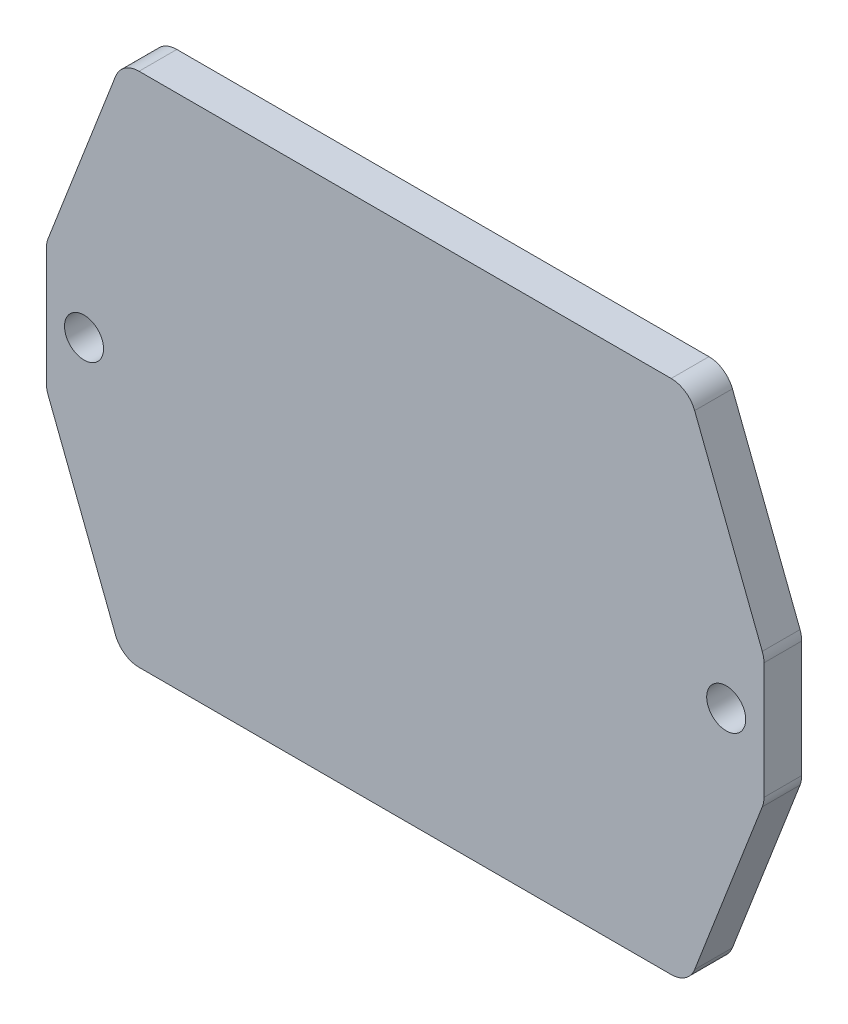
SolidWorks part; units mm, degrees
ref_plane "前视基准面" through (0, 0, 0) normal (0, 0, 1) x (1, 0, 0)
ref_plane "上视基准面" through (0, 0, 0) normal (0, 1, 0) x (1, 0, 0)
ref_plane "右视基准面" through (0, 0, 0) normal (1, 0, 0) x (0, 0, -1)
sketch "草图1" plane through (0, 0, 0) normal (0, 0, 1) x (1, 0, 0)
  line L1 (-22.5, -20.5) -> (22.5, -20.5)
  line L2 (-22.5, -20.5) -> (-22.5, 20.5)
  line L3 (-22.5, 20.5) -> (22.5, 20.5)
  line L4 (22.5, -20.5) -> (22.5, 20.5)
  line L5 (0, 20.5) -> (0, -20.5) construction
  line L6 (-22.5, 0) -> (22.5, 0) construction
  point P0 (0, 0)
  dimension "D1" = 45
  dimension "D2" = 41
extrude "凸台-拉伸1" add sketch "草图1" along normal blind 3
sketch "草图2" plane through (0, 0, 3) normal (0, 0, 1) x (1, 0, 0)
  line L0 (22.5, -20.5) -> (22.5, 20.5) construction
  line L1 (16.5, -5) -> (28.5, -5)
  line L2 (16.5, -5) -> (16.5, 5)
  line L3 (16.5, 5) -> (28.5, 5)
  line L4 (28.5, -5) -> (28.5, 5)
  line L5 (22.5, 5) -> (22.5, -5) construction
  line L6 (16.5, 0) -> (28.5, 0) construction
  line L7 (0, 20.5) -> (0, 0) construction
  line L8 (22.5, 20.5) -> (-22.5, 20.5) construction
  line L9 (-16.5, 5) -> (-28.5, 5)
  line L10 (-28.5, -5) -> (-28.5, 5)
  line L11 (-16.5, -5) -> (-28.5, -5)
  line L12 (-16.5, -5) -> (-16.5, 5)
  point P0 (22.5, 0)
  dimension "D1" = 10
  dimension "D2" = 6
extrude "凸台-拉伸2" add sketch "草图2" against normal up to surface (3 mm away) up to face at (0, 0, 0)
sketch "草图3" plane through (0, 0, 3) normal (0, 0, 1) x (1, 0, 0)
  line L0 (-22.5, 20.5) -> (-28.5, 5)
  line L1 (-28.5, 5) -> (-22.5, 5)
  line L2 (-22.5, 5) -> (-22.5, 20.5)
  line L3 (0, 0) -> (0, 20.5) construction
  line L4 (22.5, 20.5) -> (-22.5, 20.5) construction
  line L5 (22.5, 5) -> (22.5, 20.5)
  line L6 (28.5, 5) -> (22.5, 5)
  line L7 (22.5, 20.5) -> (28.5, 5)
  line L8 (0, 0) -> (28.5, 0) construction
  line L9 (28.5, -5) -> (28.5, 5) construction
  line L10 (-28.5, -5) -> (-22.5, -5)
  line L11 (-22.5, -20.5) -> (-28.5, -5)
  line L12 (-22.5, -5) -> (-22.5, -20.5)
  line L13 (22.5, -20.5) -> (28.5, -5)
  line L14 (28.5, -5) -> (22.5, -5)
  line L15 (22.5, -5) -> (22.5, -20.5)
extrude "凸台-拉伸3" add sketch "草图3" against normal up to surface (3 mm away) up to face at (0, 0, 0)
sketch "草图4" plane through (0, 0, 3) normal (0, 0, 1) x (1, 0, 0)
  line L0 (28.5, 0) -> (25.5, 0) construction
  line L1 (28.5, -5) -> (28.5, 5) construction
  line L2 (0, 0.3551) -> (0, 20.5) construction
  line L3 (22.5, 20.5) -> (-22.5, 20.5) construction
  circle A0 centre (25.5, 0) radius 1.55
  circle A1 centre (-25.5, 0) radius 1.55
  dimension "D2" = 3.1
  dimension "D1" = 3
extrude "切除-拉伸1" cut sketch "草图4" against normal blind 3
fillet "圆角1" radius 2 8 edges at (22.5, -20.5, 1.5) (28.5, -5, 1.5) (28.5, 5, 1.5) (22.5, 20.5, 1.5) (-22.5, 20.5, 1.5) (-28.5, 5, 1.5) (-28.5, -5, 1.5) (-22.5, -20.5, 1.5)
